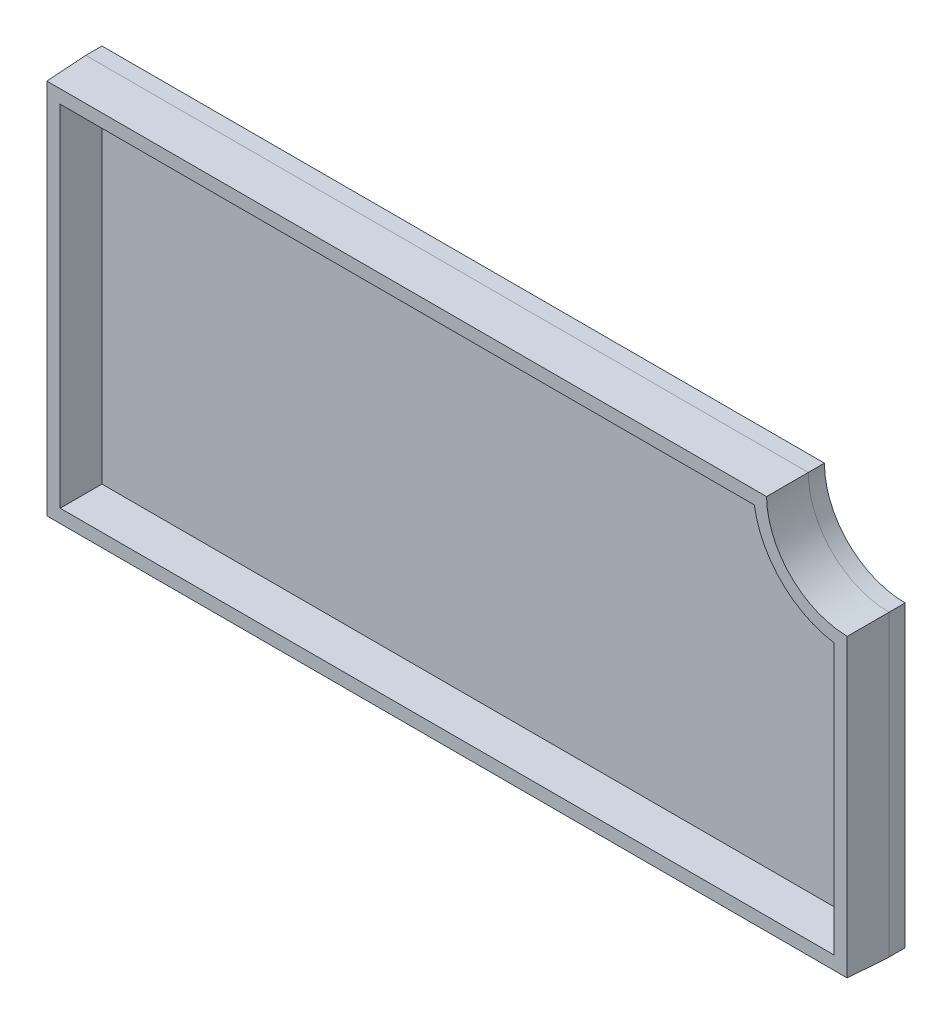
SolidWorks part; units mm, degrees
ref_plane "Plan de face" through (0, 0, 0) normal (0, 0, 1) x (1, 0, 0)
ref_plane "Plan de dessus" through (0, 0, 0) normal (0, 1, 0) x (1, 0, 0)
ref_plane "Plan de droite" through (0, 0, 0) normal (1, 0, 0) x (0, 0, -1)
sketch "Esquisse1" plane through (0, 0, 0) normal (0, 0, 1) x (1, 0, 0)
  line L0 (99.5, 37) -> (89.5, 37) construction
  line L1 (0, 0) -> (99.5, 0)
  line L2 (0, 0) -> (0, 47)
  line L3 (0, 47) -> (89.5, 47)
  line L4 (99.5, 0) -> (99.5, 37)
  line L5 (89.5, 37) -> (89.5, 47) construction
  arc A0 (89.5, 47) -> (99.5, 37) centre (99.5, 47) ccw
  dimension "D1" = 47
  dimension "D2" = 99.5
  dimension "D3" = 10
extrude "Boss.-Extru.1" add sketch "Esquisse1" along normal blind 2
sketch "Esquisse2" plane through (0, 0, 2) normal (0, 0, 1) x (1, 0, 0)
  line L0 (2, 45) -> (2, 2)
  line L1 (2, 2) -> (97.5, 2)
  line L2 (97.5, 2) -> (97.5, 35.1678)
  line L4 (0, 47) -> (0, 0)
  line L5 (0, 0) -> (99.5, 0)
  line L6 (99.5, 0) -> (99.5, 37)
  line L7 (89.5, 47) -> (0, 47)
  line L8 (0, 47) -> (0, 0)
  line L9 (0, 0) -> (99.5, 0)
  line L10 (99.5, 0) -> (99.5, 37)
  line L11 (89.5, 47) -> (0, 47)
  line L12 (87.6678, 45) -> (2, 45)
  line L13 (2, 45) -> (2, 47) construction
  line L14 (2, 2) -> (0, 2) construction
  line L15 (97.5, 2) -> (99.5, 2) construction
  line L16 (2, 2) -> (2, 0) construction
  line L17 (91.0147, 38.5147) -> (92.4289, 39.9289) construction
  arc A0 (87.6678, 45) -> (97.5, 35.1678) centre (99.5, 47) ccw
  arc A1 (89.5, 47) -> (99.5, 37) centre (99.5, 47) ccw
  arc A2 (89.5, 47) -> (99.5, 37) centre (99.5, 47) ccw
  dimension "D2" = 2
  dimension "D1" = 0
extrude "Boss.-Extru.2" add sketch "Esquisse2" along normal blind 5 draft 2
